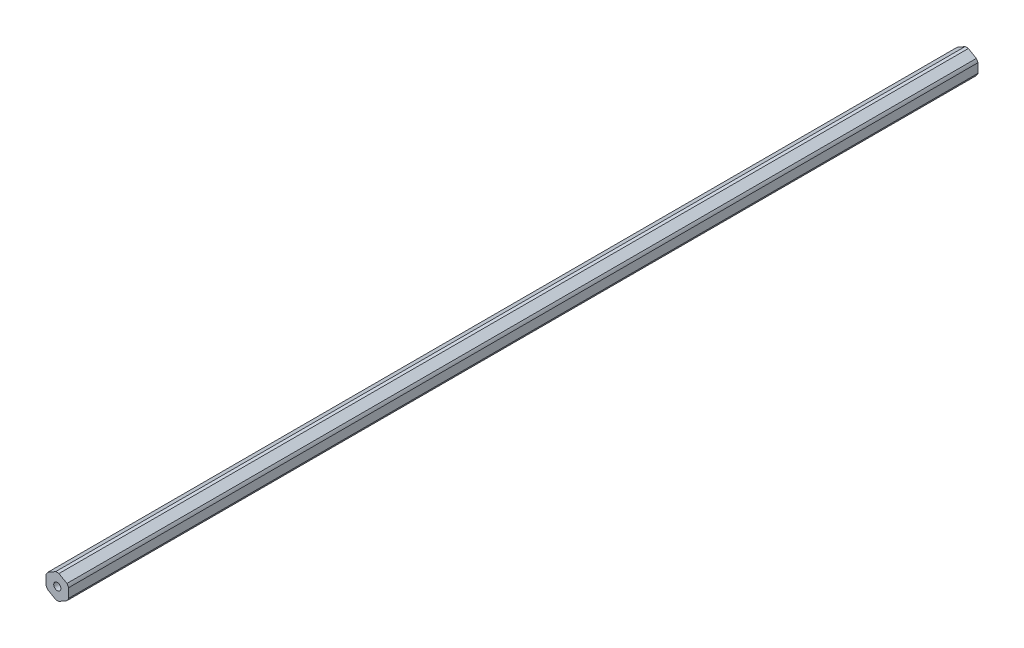
SolidWorks part; units mm, degrees
material "6061-T6 (SS)"
ref_plane "Front Plane" through (0, 0, 0) normal (0, 0, 1) x (1, 0, 0)
ref_plane "Top Plane" through (0, 0, 0) normal (0, 1, 0) x (1, 0, 0)
ref_plane "Right Plane" through (0, 0, 0) normal (1, 0, 0) x (0, 0, -1)
sketch "Sketch1" plane through (0, 0, 0) normal (0, 0, 1) x (1, 0, 0)
  line L1 (0, 7.3323) -> (-6.35, 3.6662)
  line L2 (-6.35, 3.6662) -> (-6.35, -3.6662)
  line L3 (-6.35, -3.6662) -> (0, -7.3323)
  line L4 (0, -7.3323) -> (6.35, -3.6662)
  line L5 (6.35, -3.6662) -> (6.35, 3.6662)
  line L6 (6.35, 3.6662) -> (0, 7.3323)
  circle A0 centre (0, 0) radius 6.35 construction
  circle A1 centre (0, 0) radius 6.858
  dimension "D1" = 12.7
  dimension "D2" = 13.716
extrude "Boss-Extrude1" add sketch "Sketch1" along normal mid plane 511.429 contours L5 A1 L6 L1 L2 L3 L4
sketch "Sketch2" plane through (0, 0, 255.7145) normal (0, 0, 1) x (1, 0, 0)
  circle A0 centre (0, 0) radius 2.0193
  dimension "D1" = 4.0386
extrude "Cut-Extrude1" cut sketch "Sketch2" against normal through all
